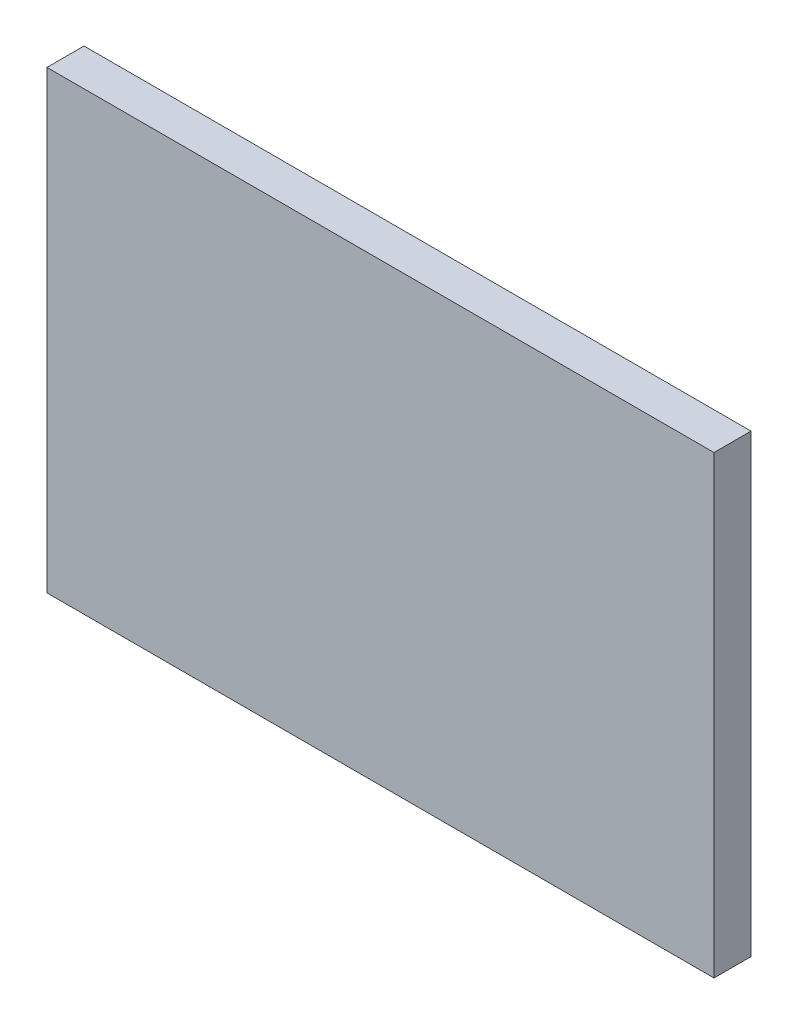
SolidWorks part; units mm, degrees
ref_plane "Front Plane" through (0, 0, 0) normal (0, 0, 1) x (1, 0, 0)
ref_plane "Top Plane" through (0, 0, 0) normal (0, 1, 0) x (1, 0, 0)
ref_plane "Right Plane" through (0, 0, 0) normal (1, 0, 0) x (0, 0, -1)
sketch "Sketch1" plane through (0, 0, 0) normal (0, 0, 1) x (1, 0, 0)
  line L1 (-57.15, 38.989) -> (57.15, 38.989)
  line L2 (-57.15, 38.989) -> (-57.15, -38.989)
  line L3 (-57.15, -38.989) -> (57.15, -38.989)
  line L4 (57.15, 38.989) -> (57.15, -38.989)
  line L5 (-57.15, 38.989) -> (57.15, -38.989) construction
  line L6 (-57.15, -38.989) -> (57.15, 38.989) construction
  point P0 (0, 0)
  dimension "D1" = 114.3
extrude "Boss-Extrude1" add sketch "Sketch1" along normal blind 6.35
